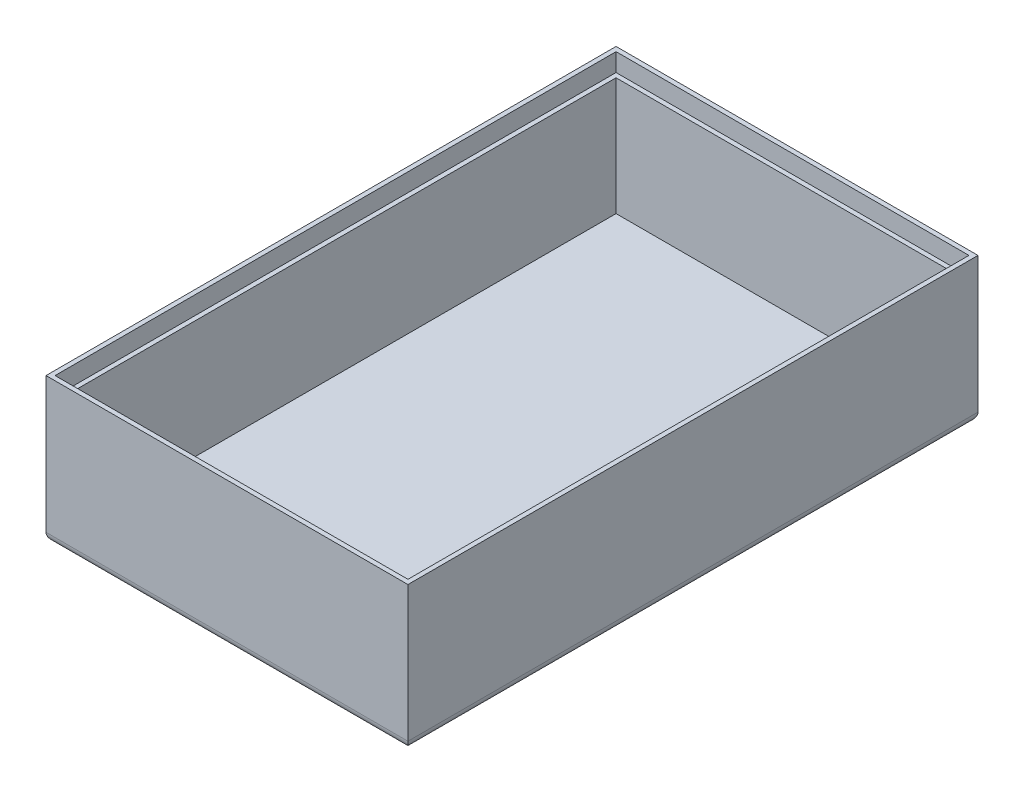
SolidWorks part; units mm, degrees
ref_plane "Front" through (0, 0, 0) normal (0, 0, 1) x (1, 0, 0)
ref_plane "Top" through (0, 0, 0) normal (0, 1, 0) x (1, 0, 0)
ref_plane "Right" through (0, 0, 0) normal (1, 0, 0) x (0, 0, -1)
sketch "Эскиз1" plane through (0, 0, 0) normal (0, 1, 0) x (1, 0, 0)
  line L1 (-1.085, 0.539) -> (38.915, 0.539)
  line L2 (-1.085, 0.539) -> (-1.085, -62.461)
  line L3 (-1.085, -62.461) -> (38.915, -62.461)
  line L4 (38.915, 0.539) -> (38.915, -62.461)
  dimension "D1" = 40
  dimension "D2" = 63
extrude "Бобышка-Вытянуть1" add sketch "Эскиз1" along normal blind 16
sketch "Эскиз2" plane through (0, 16, 0) normal (0, 1, 0) x (1, 0, 0)
  line L0 (-1.085, 0.539) -> (-1.085, -62.461) construction
  line L1 (-0.085, -0.461) -> (37.915, -0.461)
  line L2 (-0.085, -0.461) -> (-0.085, -61.461)
  line L3 (-0.085, -61.461) -> (37.915, -61.461)
  line L4 (37.915, -0.461) -> (37.915, -61.461)
  line L5 (38.915, 0.539) -> (-1.085, 0.539) construction
  dimension "D1" = 38
  dimension "D2" = 61
  dimension "D3" = 1
  dimension "D4" = 1
extrude "Вырез-Вытянуть2" cut sketch "Эскиз2" against normal blind 15
fillet "Скругление2" radius 1 4 edges at (38.915, 0, 30.961) (18.915, 0, 62.461) (-1.085, 0, 30.961) (18.915, 0, -0.539)
sketch "Эскиз5" plane through (0, 0, 61.461) normal (0, 0, -1) x (-1, 0, 0)
  line L0 (-37.915, 1) -> (-37.915, 16) construction
  line L1 (-37.915, 16) -> (0.085, 16)
  line L2 (-37.915, 16) -> (-37.915, 14)
  line L3 (-37.915, 14) -> (0.085, 14)
  line L4 (0.085, 16) -> (0.085, 14)
  line L5 (0.085, 1) -> (0.085, 16) construction
  line L6 (0.085, 16) -> (-37.915, 16) construction
  dimension "D1" = 2
  dimension "D2" = 0
extrude "Вырез-Вытянуть4" cut sketch "Эскиз5" against normal blind 0.5
sketch "Эскиз6" plane through (-0.085, 0, 0) normal (1, 0, 0) x (0, 0, -1)
  line L2 (-0.461, 16) -> (-61.961, 16)
  line L3 (-0.461, 16) -> (-0.461, 14)
  line L4 (-0.461, 14) -> (-61.961, 14)
  line L5 (-61.961, 16) -> (-61.961, 14)
  dimension "D1" = 0
  dimension "D2" = 2
extrude "Вырез-Вытянуть5" cut sketch "Эскиз6" against normal blind 0.5
sketch "Эскиз7" plane through (0, 0, 0.461) normal (0, 0, 1) x (1, 0, 0)
  line L0 (-0.585, 14) -> (-0.585, 16) construction
  line L1 (37.915, 16) -> (-0.585, 16)
  line L2 (37.915, 16) -> (37.915, 14)
  line L3 (37.915, 14) -> (-0.585, 14)
  line L4 (-0.585, 16) -> (-0.585, 14)
  dimension "D1" = 2
  dimension "D2" = 0
extrude "Вырез-Вытянуть6" cut sketch "Эскиз7" against normal blind 0.5
sketch "Эскиз8" plane through (37.915, 0, 0) normal (-1, 0, 0) x (0, 0, 1)
  line L0 (61.961, 16) -> (61.961, 14) construction
  line L1 (-0.039, 16) -> (61.961, 16)
  line L2 (-0.039, 16) -> (-0.039, 14)
  line L3 (-0.039, 14) -> (61.961, 14)
  line L4 (61.961, 16) -> (61.961, 14)
extrude "Вырез-Вытянуть7" cut sketch "Эскиз8" against normal blind 0.5
